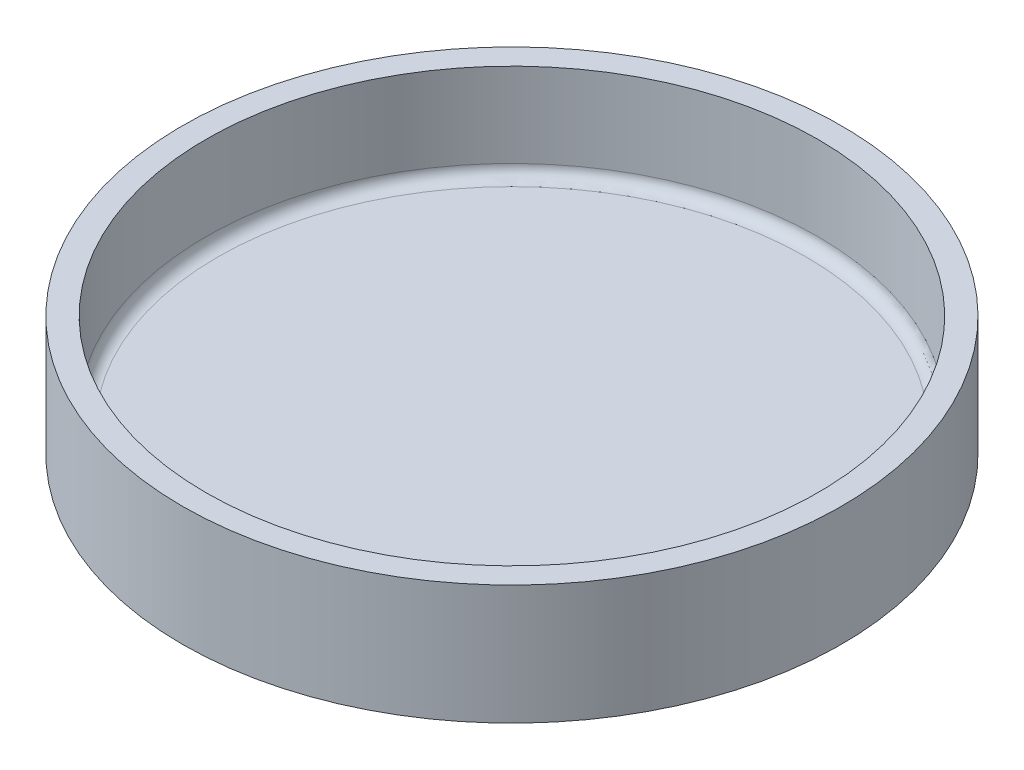
SolidWorks part; units mm, degrees
ref_plane "Front Plane" through (0, 0, 0) normal (0, 0, 1) x (1, 0, 0)
ref_plane "Top Plane" through (0, 0, 0) normal (0, 1, 0) x (1, 0, 0)
ref_plane "Right Plane" through (0, 0, 0) normal (1, 0, 0) x (0, 0, -1)
sketch "Sketch1" plane through (0, 0, 0) normal (0, 1, 0) x (1, 0, 0)
  circle A0 centre (0, 0) radius 55
  circle A1 centre (0, 0) radius 65
  circle A2 centre (0, 0) radius 70
  dimension "D1" = 110
  dimension "D2" = 10
  dimension "D3" = 5
extrude "Boss-Extrude1" add sketch "Sketch1" along normal blind 5 contours A2 A1 | A1 A0 | A0
sketch "Sketch2" plane through (0, 5, 0) normal (0, 1, 0) x (1, 0, 0)
  circle A2 centre (0, 0) radius 65
  circle A3 centre (0, 0) radius 65
  circle M2 centre (0, 0) radius 70
  dimension "D1" = 5
extrude "Boss-Extrude2" add sketch "Sketch2" along normal blind 20.4 contours A3 M2
fillet "Fillet1" radius 2.5 1 edges at (0, 5, 65)
